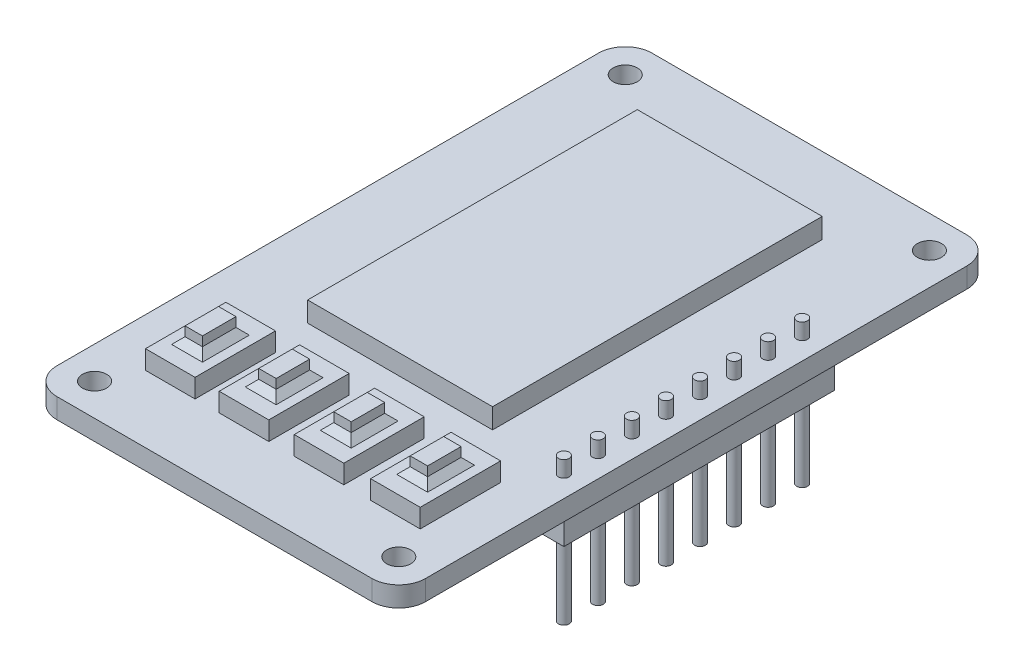
SolidWorks part; units mm, degrees
ref_plane "Спереди" through (0, 0, 0) normal (0, 0, 1) x (1, 0, 0)
ref_plane "Сверху" through (0, 0, 0) normal (0, 1, 0) x (1, 0, 0)
ref_plane "Справа" through (0, 0, 0) normal (1, 0, 0) x (0, 0, -1)
sketch "Эскиз1" plane through (0, 0, 0) normal (0, 1, 0) x (1, 0, 0)
  line L0 (11.75, 22.2) -> (-11.75, 22.2)
  line L1 (13.75, 20.2) -> (13.75, -20.2)
  line L2 (11.75, -22.2) -> (-11.75, -22.2)
  line L3 (-13.75, 20.2) -> (-13.75, -20.2)
  line L4 (13.75, 0) -> (-13.75, 0) construction
  line L5 (6.65, 16.5) -> (-7.15, 16.5) construction
  line L6 (6.65, 16.5) -> (6.65, -8.1) construction
  line L7 (6.65, -8.1) -> (-7.15, -8.1) construction
  line L8 (-7.15, 16.5) -> (-7.15, -8.1) construction
  circle A0 centre (11.35, 19.8) radius 0.9
  circle A1 centre (-11.35, 19.8) radius 0.9
  circle A2 centre (-11.35, -19.8) radius 0.9
  circle A3 centre (11.35, -19.8) radius 0.9
  arc A4 (13.75, -20.2) -> (11.75, -22.2) centre (11.75, -20.2) cw
  arc A5 (-11.75, -22.2) -> (-13.75, -20.2) centre (-11.75, -20.2) cw
  arc A6 (-11.75, 22.2) -> (-13.75, 20.2) centre (-11.75, 20.2) ccw
  arc A7 (11.75, 22.2) -> (13.75, 20.2) centre (11.75, 20.2) cw
  dimension "D7" = 1.8
  dimension "D12" = 1.8
  dimension "D13" = 2
  dimension "D1" = 44.4
  dimension "D2" = 27.5
  dimension "D3" = 7.1
  dimension "D4" = 6.6
  dimension "D5" = 5.7
  dimension "D6" = 24.6
  dimension "D8" = 2.4
  dimension "D9" = 2.4
  dimension "D10" = 2.4
  dimension "D11" = 2.4
extrude "Бобышка-Вытянуть1" add sketch "Эскиз1" along normal blind 1.5
sketch "Эскиз2" plane through (0, 1.5, 0) normal (0, 1, 0) x (1, 0, 0)
  line L0 (11.75, 22.2) -> (-11.75, 22.2) construction
  line L1 (13.75, 20.2) -> (13.75, -20.2) construction
  line L2 (11.75, -22.2) -> (-11.75, -22.2) construction
  line L3 (-13.75, 20.2) -> (-13.75, -20.2) construction
  line L4 (11.75, 22.2) -> (-11.75, 22.2)
  line L5 (-13.75, 20.2) -> (-13.75, -20.2)
  line L6 (-11.75, -22.2) -> (11.75, -22.2)
  line L7 (13.75, -20.2) -> (13.75, 20.2)
  line L8 (11.75, 22.2) -> (-11.75, 22.2) construction
  line L9 (-13.75, 20.2) -> (-13.75, -20.2) construction
  line L10 (-11.75, -22.2) -> (11.75, -22.2) construction
  line L11 (13.75, -20.2) -> (13.75, 20.2) construction
  line L12 (13.75, 0) -> (-13.75, 0) construction
  line L13 (6.65, 16.5) -> (-7.15, 16.5)
  line L14 (6.65, 16.5) -> (6.65, -8.1)
  line L15 (6.65, -8.1) -> (-7.15, -8.1)
  line L16 (-7.15, 16.5) -> (-7.15, -8.1)
  circle A0 centre (11.35, 19.8) radius 0.9 construction
  circle A1 centre (-11.35, -19.8) radius 0.9
  circle A2 centre (-11.35, -19.8) radius 0.9 construction
  circle A3 centre (-11.35, 19.8) radius 0.9
  circle A4 centre (-11.35, 19.8) radius 0.9 construction
  circle A5 centre (11.35, 19.8) radius 0.9
  circle A6 centre (11.35, 19.8) radius 0.9 construction
  circle A7 centre (11.35, -19.8) radius 0.9
  circle A8 centre (11.35, -19.8) radius 0.9 construction
  circle A9 centre (-11.35, 19.8) radius 0.9 construction
  circle A10 centre (-11.35, -19.8) radius 0.9 construction
  circle A11 centre (11.35, -19.8) radius 0.9 construction
  arc A12 (-11.75, 22.2) -> (-13.75, 20.2) centre (-11.75, 20.2) ccw
  arc A13 (-13.75, -20.2) -> (-11.75, -22.2) centre (-11.75, -20.2) ccw
  arc A14 (11.75, -22.2) -> (13.75, -20.2) centre (11.75, -20.2) ccw
  arc A15 (13.75, 20.2) -> (11.75, 22.2) centre (11.75, 20.2) ccw
  arc A16 (-11.75, 22.2) -> (-13.75, 20.2) centre (-11.75, 20.2) ccw construction
  arc A17 (-13.75, -20.2) -> (-11.75, -22.2) centre (-11.75, -20.2) ccw construction
  arc A18 (11.75, -22.2) -> (13.75, -20.2) centre (11.75, -20.2) ccw construction
  arc A19 (13.75, 20.2) -> (11.75, 22.2) centre (11.75, 20.2) ccw construction
  arc A20 (13.75, -20.2) -> (11.75, -22.2) centre (11.75, -20.2) cw construction
  arc A21 (-11.75, -22.2) -> (-13.75, -20.2) centre (-11.75, -20.2) cw construction
  arc A22 (-11.75, 22.2) -> (-13.75, 20.2) centre (-11.75, 20.2) ccw construction
  arc A23 (11.75, 22.2) -> (13.75, 20.2) centre (11.75, 20.2) cw construction
  dimension "D10" = 1.8
  dimension "D15" = 1.8
  dimension "D16" = 2
  dimension "D6" = 44.4
  dimension "D7" = 27.5
  dimension "D8" = 5.7
  dimension "D9" = 24.6
  dimension "D11" = 2.4
  dimension "D12" = 2.4
  dimension "D13" = 2.4
  dimension "D14" = 2.4
  dimension "D17" = 6.6
  dimension "D18" = 7.1
  dimension "D1" = 0
  dimension "D2" = 0
  dimension "D3" = 0
  dimension "D4" = 0
  dimension "D5" = 0
extrude "Бобышка-Вытянуть2" add sketch "Эскиз2" along normal blind 1.5
sketch "Эскиз3" plane through (0, 1.5, 0) normal (0, 1, 0) x (1, 0, 0)
  line L0 (13.75, -20.2) -> (13.75, 20.2) construction
  line L1 (10.35, -11.2) -> (6.65, -11.2)
  line L2 (10.35, -11.2) -> (10.35, -17.2)
  line L3 (10.35, -17.2) -> (6.65, -17.2)
  line L4 (6.65, -11.2) -> (6.65, -17.2)
  line L5 (-11.75, -22.2) -> (11.75, -22.2) construction
  line L6 (4.65, -11.2) -> (4.65, -17.2)
  line L7 (4.65, -11.2) -> (0.95, -11.2)
  line L8 (4.65, -17.2) -> (0.95, -17.2)
  line L9 (0.95, -11.2) -> (0.95, -17.2)
  line L10 (-0.95, -11.2) -> (-0.95, -17.2)
  line L11 (-0.95, -11.2) -> (-4.65, -11.2)
  line L12 (-0.95, -17.2) -> (-4.65, -17.2)
  line L13 (-4.65, -11.2) -> (-4.65, -17.2)
  line L14 (-6.45, -11.2) -> (-6.45, -17.2)
  line L15 (-6.45, -11.2) -> (-10.15, -11.2)
  line L16 (-6.45, -17.2) -> (-10.15, -17.2)
  line L17 (-10.15, -11.2) -> (-10.15, -17.2)
  dimension "D1" = 3.7
  dimension "D2" = 6
  dimension "D3" = 3.4
  dimension "D4" = 5
  dimension "D5" = 3.7
  dimension "D6" = 6
  dimension "D7" = 5
  dimension "D8" = 5
  dimension "D9" = 3.7
  dimension "D10" = 6
  dimension "D11" = 6
  dimension "D12" = 3.7
  dimension "D13" = 5
  dimension "D14" = 20.5
  dimension "D15" = 9.2
  dimension "D16" = 9.4
extrude "Бобышка-Вытянуть3" add sketch "Эскиз3" along normal blind 1.4
sketch "Эскиз4" plane through (0, 2.9, 0) normal (0, 1, 0) x (1, 0, 0)
  line L0 (6.65, -11.2) -> (6.65, -17.2) construction
  line L1 (9.15, -12.95) -> (7.85, -12.95)
  line L2 (9.15, -12.95) -> (9.15, -15.45)
  line L3 (9.15, -15.45) -> (7.85, -15.45)
  line L4 (7.85, -12.95) -> (7.85, -15.45)
  line L5 (10.35, -11.2) -> (6.65, -11.2) construction
  line L6 (2.15, -12.95) -> (2.15, -15.45)
  line L7 (3.45, -12.95) -> (3.45, -15.45)
  line L8 (3.45, -12.95) -> (2.15, -12.95)
  line L9 (3.45, -15.45) -> (2.15, -15.45)
  line L10 (-3.45, -12.95) -> (-3.45, -15.45)
  line L11 (-2.15, -12.95) -> (-2.15, -15.45)
  line L12 (-2.15, -12.95) -> (-3.45, -12.95)
  line L13 (-2.15, -15.45) -> (-3.45, -15.45)
  line L14 (-8.95, -12.95) -> (-8.95, -15.45)
  line L15 (-7.65, -12.95) -> (-7.65, -15.45)
  line L16 (-7.65, -12.95) -> (-8.95, -12.95)
  line L17 (-7.65, -15.45) -> (-8.95, -15.45)
  point P6 (6.65, -14.2)
  point P9 (8.5, -11.2)
  dimension "D1" = 2.5
  dimension "D2" = 1.3
  dimension "D3" = 1.25
  dimension "D4" = 0.65
extrude "Бобышка-Вытянуть4" add sketch "Эскиз4" along normal blind 1.2
chamfer "Фаска1" distance 0.5 angle 45 16 edges at (-7.65, 2.9, 14.2) (-8.3, 2.9, 12.95) (-8.95, 2.9, 14.2) (-8.3, 2.9, 15.45) (-2.15, 2.9, 14.2) (-2.8, 2.9, 15.45) (-3.45, 2.9, 14.2) (-2.8, 2.9, 12.95) (2.15, 2.9, 14.2) (2.8, 2.9, 12.95) (3.45, 2.9, 14.2) (2.8, 2.9, 15.45) (8.5, 2.9, 15.45) (9.15, 2.9, 14.2) (8.5, 2.9, 12.95) (7.85, 2.9, 14.2)
sketch "Эскиз5" plane through (0, 1.5, 0) normal (0, 1, 0) x (1, 0, 0)
  line L0 (11.75, 22.2) -> (-11.75, 22.2) construction
  line L1 (13.75, -20.2) -> (13.75, 20.2) construction
  circle A0 centre (12.15, 9.5) radius 0.4
  circle A1 centre (12.15, 6.96) radius 0.4
  circle A2 centre (12.15, 4.42) radius 0.4
  circle A3 centre (12.15, 1.88) radius 0.4
  circle A4 centre (12.15, -0.66) radius 0.4
  circle A5 centre (12.15, -3.2) radius 0.4
  circle A6 centre (12.15, -5.74) radius 0.4
  circle A7 centre (12.15, -8.28) radius 0.4
  point P20 (0, 0)
  dimension "D1" = 0.8
  dimension "D3" = 12.7
  dimension "D4" = 1.6
  dimension "D2" = 8
extrude "Бобышка-Вытянуть5" add sketch "Эскиз5" along normal blind 1.2 and the other way blind 9.5
sketch "Эскиз6" plane through (0, 0, 0) normal (0, -1, 0) x (1, 0, 0)
  line L1 (13.35, 9.48) -> (10.95, 9.48)
  line L2 (13.35, 9.48) -> (13.35, -10.7)
  line L3 (13.35, -10.7) -> (10.95, -10.7)
  line L4 (10.95, 9.48) -> (10.95, -10.7)
  circle A0 centre (12.15, 8.28) radius 0.4 construction
  circle A1 centre (12.15, -9.5) radius 0.4 construction
  circle A2 centre (12.15, -6.96) radius 0.4 construction
  circle A3 centre (12.15, -4.42) radius 0.4 construction
  circle A4 centre (12.15, -1.88) radius 0.4 construction
  circle A5 centre (12.15, 0.66) radius 0.4 construction
  circle A6 centre (12.15, 3.2) radius 0.4 construction
  circle A7 centre (12.15, 5.74) radius 0.4 construction
  circle A8 centre (12.15, -9.5) radius 0.4
  circle A9 centre (12.15, -6.96) radius 0.4
  circle A10 centre (12.15, -4.42) radius 0.4
  circle A11 centre (12.15, -1.88) radius 0.4
  circle A12 centre (12.15, 0.66) radius 0.4
  circle A13 centre (12.15, 3.2) radius 0.4
  circle A14 centre (12.15, 5.74) radius 0.4
  circle A15 centre (12.15, 8.28) radius 0.4
  dimension "D2" = 1.2
  dimension "D1" = 2.4
  dimension "D3" = 1.2
  dimension "D4" = 1.2
extrude "Бобышка-Вытянуть6" add sketch "Эскиз6" along normal blind 2
